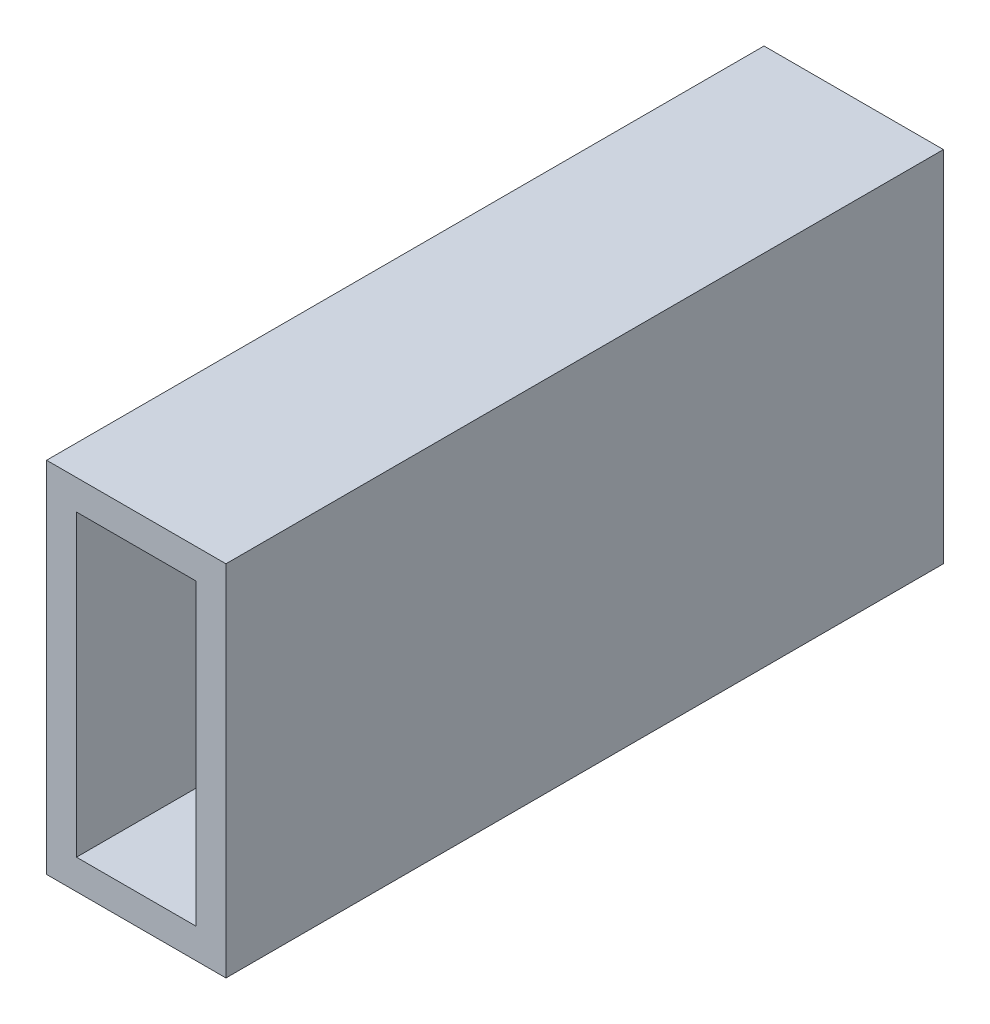
SolidWorks part; units mm, degrees
ref_plane "Front Plane" through (0, 0, 0) normal (0, 0, 1) x (1, 0, 0)
ref_plane "Top Plane" through (0, 0, 0) normal (0, 1, 0) x (1, 0, 0)
ref_plane "Right Plane" through (0, 0, 0) normal (1, 0, 0) x (0, 0, -1)
sketch "Sketch1" plane through (0, 0, 0) normal (0, 0, 1) x (1, 0, 0)
  line L0 (6.35, -15.875) -> (6.35, 15.875)
  line L1 (-9.525, -19.05) -> (9.525, -19.05)
  line L2 (-9.525, -19.05) -> (-9.525, 19.05)
  line L3 (-9.525, 19.05) -> (9.525, 19.05)
  line L4 (9.525, -19.05) -> (9.525, 19.05)
  line L5 (-9.525, -19.05) -> (9.525, 19.05) construction
  line L6 (-9.525, 19.05) -> (9.525, -19.05) construction
  line L7 (-6.35, 15.875) -> (6.35, 15.875)
  line L8 (-6.35, -15.875) -> (-6.35, 15.875)
  line L9 (-6.35, -15.875) -> (6.35, -15.875)
  point P0 (0, 0)
  dimension "D1" = 38.1
  dimension "D2" = 19.05
  dimension "D3" = 3.175
extrude "Boss-Extrude1" add sketch "Sketch1" along normal blind 76.2
